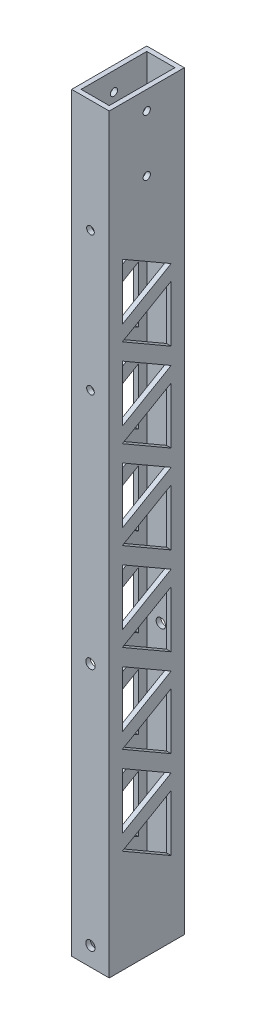
SolidWorks part; units mm, degrees
material "5052-O"
ref_plane "Front Plane" through (0, 0, 0) normal (0, 0, 1) x (1, 0, 0)
ref_plane "Top Plane" through (0, 0, 0) normal (0, 1, 0) x (1, 0, 0)
ref_plane "Right Plane" through (0, 0, 0) normal (1, 0, 0) x (0, 0, -1)
sketch "Sketch1" plane through (0, 0, 0) normal (0, 1, 0) x (1, 0, 0)
  line L0 (3.175, 3.175) -> (3.175, 47.625)
  line L1 (0, 0) -> (25.4, 0)
  line L2 (0, 0) -> (0, 50.8)
  line L3 (0, 50.8) -> (25.4, 50.8)
  line L4 (25.4, 0) -> (25.4, 50.8)
  line L5 (3.175, 47.625) -> (22.225, 47.625)
  line L6 (22.225, 3.175) -> (22.225, 47.625)
  line L7 (3.175, 3.175) -> (22.225, 3.175)
  dimension "D2" = 50.8
  dimension "D3" = 25.4
  dimension "D1" = 3.175
extrude "Boss-Extrude1" add sketch "Sketch1" along normal blind 508
sketch "Sketch3" plane through (0, 0, 0) normal (0, 0, 1) x (1, 0, 0)
  line L0 (12.7, 0) -> (12.7, 267.686) construction
  line L1 (0, 0) -> (25.4, 0) construction
  line L3 (13.97, 0) -> (-13.97, 0) construction
  circle A0 centre (12.7, 177.8) radius 3.175
  circle A1 centre (12.7, 12.7) radius 3.175
  dimension "D1" = 6.35
  dimension "D2" = 177.8
  dimension "D3" = 12.7
extrude "Cut-Extrude1" cut sketch "Sketch3" against normal through all
sketch "Sketch4" plane through (0, 0, 0) normal (-1, 0, 0) x (0, 0, 1)
  circle A0 centre (-25.4, 457.2) radius 2.4638
  circle A1 centre (-25.4, 495.3) radius 2.4638
  dimension "D1" = 4.9276
extrude "Cut-Extrude2" cut sketch "Sketch4" against normal through all
sketch "Sketch5" plane through (25.4, 0, 0) normal (1, 0, 0) x (0, 0, -1)
  line L0 (25.4, 508) -> (25.4, 0) construction
  line L1 (0, 508) -> (50.8, 508) construction
  line L2 (13.97, 0) -> (-13.97, 0) construction
  line L4 (41.91, 88.9282) -> (8.89, 69.8641)
  line L5 (8.89, 69.8641) -> (41.91, 50.8)
  line L6 (41.91, 50.8) -> (41.91, 88.9282)
  line L7 (41.91, 99.1935) -> (8.89, 118.2576)
  line L8 (8.89, 118.2576) -> (8.89, 80.1294)
  line L9 (8.89, 80.1294) -> (41.91, 99.1935)
  line L10 (50.8, 508) -> (50.8, 0) construction
  line L11 (0, 508) -> (0, 0) construction
  circle A0 centre (30.9033, 69.8641) radius 11.0067 construction
  circle A1 centre (19.8967, 99.1935) radius 11.0067 construction
  point P7 (25.4, 79.3962)
  point P12 (25.4, 60.3321)
  point P14 (25.4, 108.7256)
  point P19 (25.4, 89.6614)
  dimension "D1" = 8.89
  dimension "D2" = 8.89
  dimension "D3" = 8.89
  dimension "D4" = 50.8
extrude "Cut-Extrude3" cut sketch "Sketch5" against normal through all
pattern_linear "LPattern1" count 6 spacing 59.69 along (0, 1, 0) of "Cut-Extrude3"
sketch "Sketch6" plane through (0, 0, -50.8) normal (0, 0, -1) x (-1, 0, 0)
  line L0 (-12.7, 508) -> (-12.7, 319.09) construction
  line L1 (0, 508) -> (-25.4, 508) construction
  circle A0 centre (-12.7, 431.8) radius 2.5797
  circle A1 centre (-12.7, 338.0533) radius 2.5797
  dimension "D1" = 5.1594
  dimension "D2" = 93.7467
  dimension "D3" = 76.2
extrude "Cut-Extrude4" cut sketch "Sketch6" against normal through all
